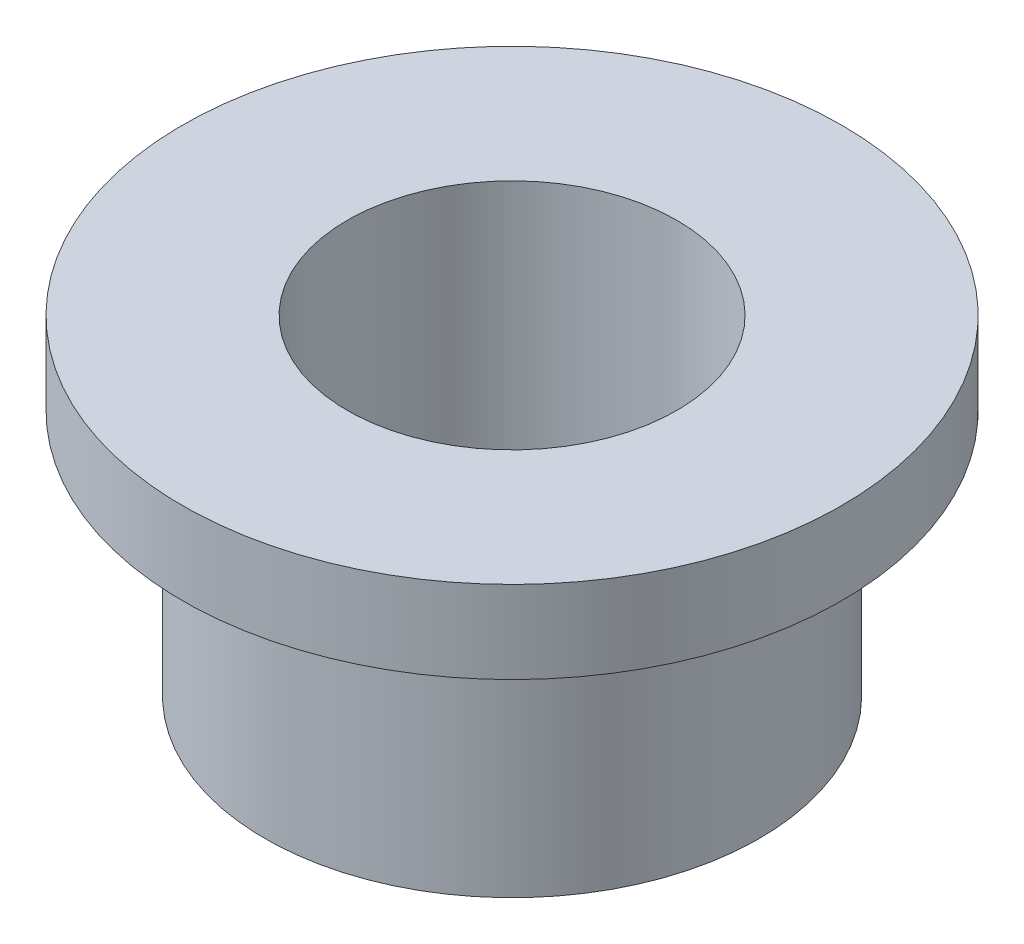
SolidWorks part; units mm, degrees
material "Phosphor bronze 10% D, UNS C52400"
ref_plane "Front Plane" through (0, 0, 0) normal (0, 0, 1) x (1, 0, 0)
ref_plane "Top Plane" through (0, 0, 0) normal (0, 1, 0) x (1, 0, 0)
ref_plane "Right Plane" through (0, 0, 0) normal (1, 0, 0) x (0, 0, -1)
sketch "Sketch1" plane through (0, 0, 0) normal (0, 0, 1) x (1, 0, 0)
  line L0 (0, 0) -> (0, 12.7) construction
  line L1 (6.35, 0) -> (6.35, 12.7)
  line L2 (6.35, 12.7) -> (12.7, 12.7)
  line L3 (12.7, 12.7) -> (12.7, 9.525)
  line L4 (12.7, 9.525) -> (9.525, 9.525)
  line L5 (9.525, 9.525) -> (9.525, 0)
  line L6 (9.525, 0) -> (6.35, 0)
  dimension "D2" = 12.7
  dimension "D3" = 12.7
  dimension "D4" = 3.175
  dimension "D5" = 9.525
  dimension "D1" = 6.35
revolve "Revolve1" add sketch "Sketch1" angle 360 about L0
